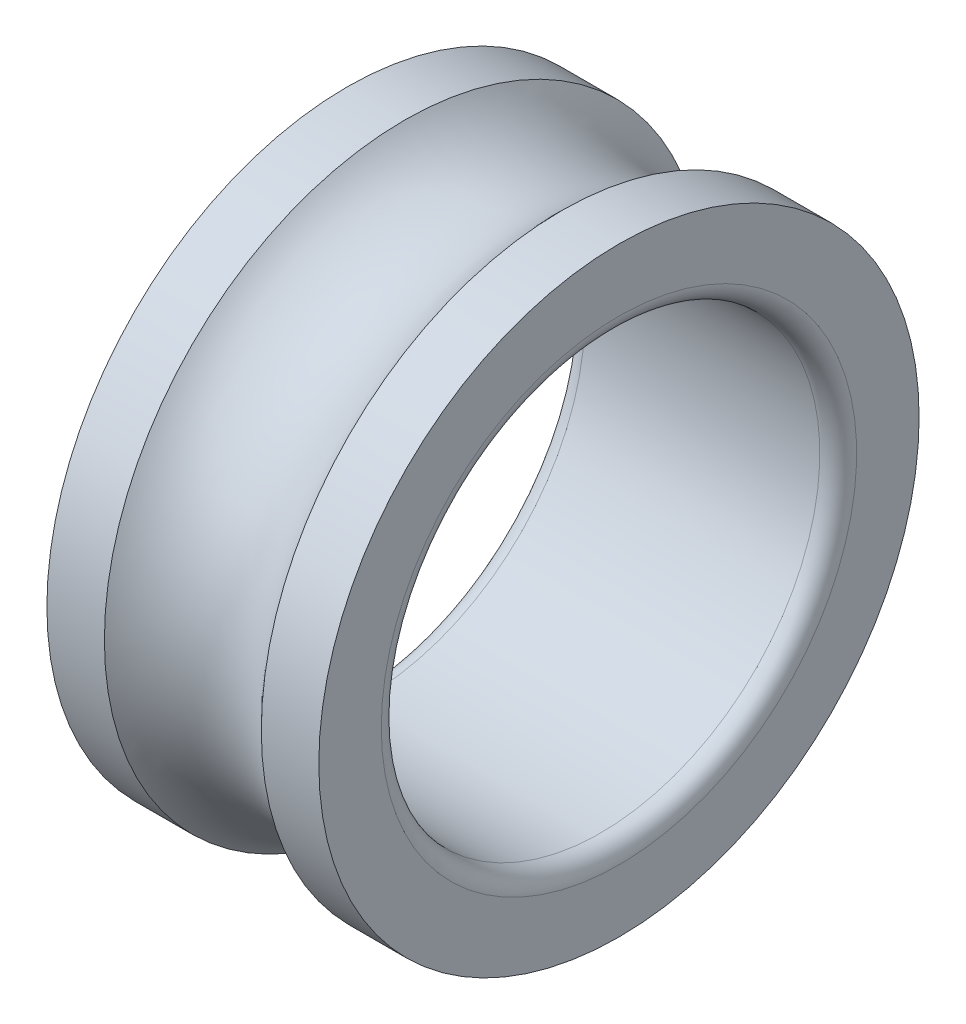
SolidWorks part; units mm, degrees
ref_plane "Front Plane" through (0, 0, 0) normal (0, 0, 1) x (1, 0, 0)
ref_plane "Top Plane" through (0, 0, 0) normal (0, 1, 0) x (1, 0, 0)
ref_plane "Right Plane" through (0, 0, 0) normal (1, 0, 0) x (0, 0, -1)
sketch "Sketch1" plane through (0, 0, 0) normal (0, 0, 1) x (1, 0, 0)
  line L0 (-9.9067, 0) -> (18.382, 0) construction
  line L1 (18.382, 0) -> (-26.0867, 0) construction
  line L10 (0, 0) -> (0, 25) construction
  line L11 (16.6796, 25) -> (-10.1204, 25)
  line L12 (18.7796, 27.1) -> (18.7796, 34.221)
  line L13 (18.7796, 34.221) -> (12.2239, 34.221)
  line L14 (-12.2204, 27.1) -> (-12.2204, 34.221)
  line L15 (18.7796, 25) -> (-12.2204, 34.221) construction
  line L16 (18.7796, 34.221) -> (-12.2204, 25) construction
  line L17 (-5.6647, 34.221) -> (-12.2204, 34.221)
  arc A0 (12.2239, 34.221) -> (-5.6647, 34.221) centre (3.2796, 42.221) cw
  arc A1 (16.6796, 25) -> (18.7796, 27.1) centre (16.6796, 27.1) ccw
  arc A2 (-10.1204, 25) -> (-12.2204, 27.1) centre (-10.1204, 27.1) cw
  point P3 (3.2796, 29.6105)
  dimension "D5" = 12
  dimension "D6" = 2.1
  dimension "D1" = 31
  dimension "D2" = 25
  dimension "D3" = 34.221
  dimension "D4" = 8
revolve "Revolve1" add sketch "Sketch1" angle 360 about L0
